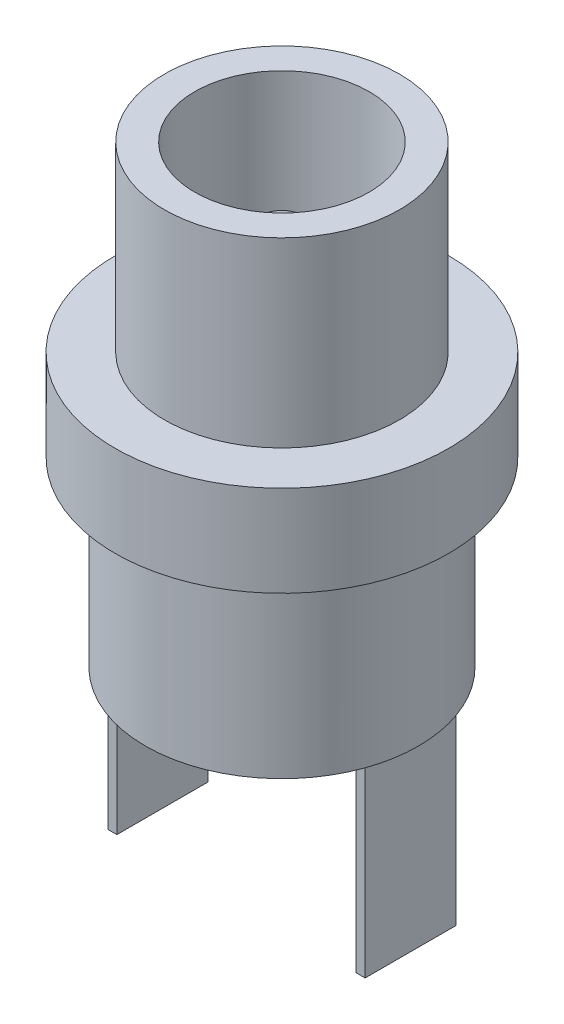
SolidWorks part; units mm, degrees
material "1023 Kohlenstoffstahlblech (SS)"
ref_plane "Ebene vorne" through (0, 0, 0) normal (0, 0, 1) x (1, 0, 0)
ref_plane "Ebene oben" through (0, 0, 0) normal (0, 1, 0) x (1, 0, 0)
ref_plane "Ebene rechts" through (0, 0, 0) normal (1, 0, 0) x (0, 0, -1)
sketch "Skizze1" plane through (0, 0, 0) normal (0, 0, 1) x (1, 0, 0)
  line L0 (0, 0) -> (-3.875, 0) construction
  line L1 (-3.875, 0) -> (-3.875, -6)
  line L2 (-3.875, -6) -> (-5.5, -6)
  line L3 (-5.5, -6) -> (-5.5, -9)
  line L4 (-5.5, -9) -> (-4.5, -9)
  line L5 (-4.5, -9) -> (-4.5, -15)
  line L6 (-4.5, -15) -> (0, -15)
  line L7 (0, -15) -> (0, 0) construction
  line L8 (0, -15) -> (0, -2.3)
  line L9 (0, -2.3) -> (-1, -2.3)
  line L10 (-1, -2.3) -> (-1, -10)
  line L11 (-1, -10) -> (-2.875, -10)
  line L12 (-2.875, -10) -> (-2.875, 0)
  line L13 (-2.875, 0) -> (-3.875, 0)
  dimension "D1" = 6
  dimension "D2" = 3
  dimension "D3" = 6
  dimension "D4" = 3.875
  dimension "D5" = 5.5
  dimension "D6" = 4.5
  dimension "D7" = 1
  dimension "D8" = 1
  dimension "D9" = 2.3
  dimension "D10" = 10
revolve "Rotation1" add sketch "Skizze1" angle 360 about L7
sketch "Skizze2" plane through (0, -15, 0) normal (0, -1, 0) x (1, 0, 0)
  line L0 (-3.9426, 0) -> (0, 0) construction
  line L1 (-4.2426, 1.5) -> (-3.9426, 1.5)
  line L2 (-4.2426, 1.5) -> (-4.2426, -1.5)
  line L3 (-4.2426, -1.5) -> (-3.9426, -1.5)
  line L4 (-3.9426, 1.5) -> (-3.9426, -1.5)
  line L5 (3.9426, 1.5) -> (4.2426, 1.5)
  line L6 (3.9426, 1.5) -> (3.9426, -1.5)
  line L7 (3.9426, -1.5) -> (4.2426, -1.5)
  line L8 (4.2426, 1.5) -> (4.2426, -1.5)
  line L9 (1.5, -3.9426) -> (-1.5, -3.9426)
  line L10 (1.5, -3.9426) -> (1.5, -4.2426)
  line L11 (1.5, -4.2426) -> (-1.5, -4.2426)
  line L12 (-1.5, -3.9426) -> (-1.5, -4.2426)
  line L13 (0, 0) -> (3.9426, 0) construction
  line L14 (0, 0) -> (0, -3.9426) construction
  circle A0 centre (0, 0) radius 4.5 construction
  dimension "D1" = 3
  dimension "D2" = 0.3
  dimension "D3" = 0.3
  dimension "D4" = 3
  dimension "D5" = 3
  dimension "D6" = 0.3
extrude "Aufsatz-Linear austragen1" add sketch "Skizze2" along normal blind 6
fillet "Verrundung1" radius 0.75 1 edges at (0, -2.3, -1)
